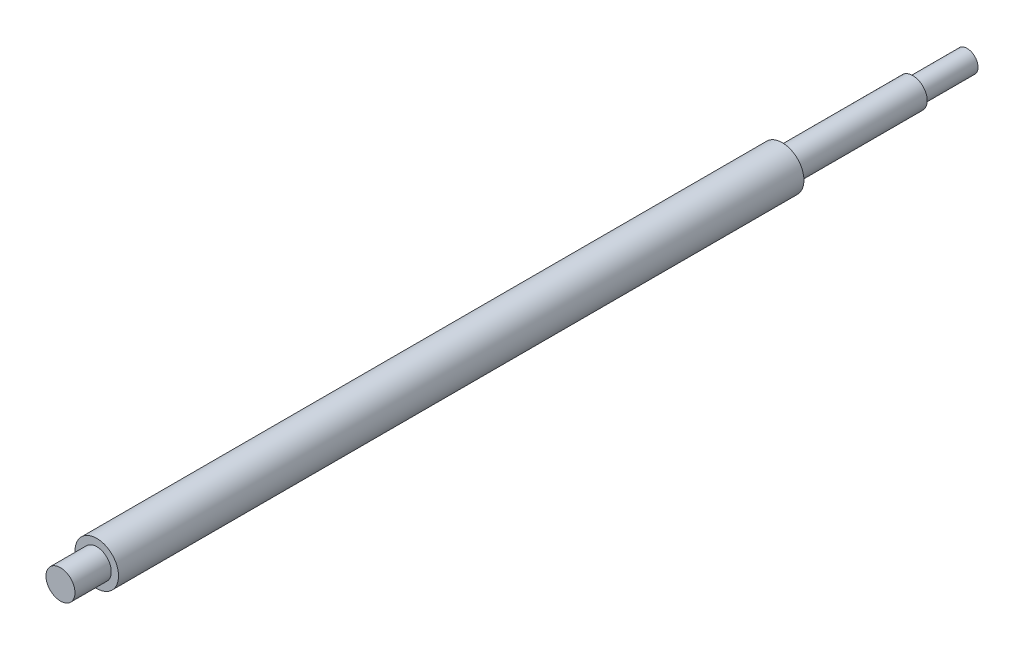
SolidWorks part; units mm, degrees
material "Легированная сталь (SS)"
ref_plane "Front Plane" through (0, 0, 0) normal (0, 0, 1) x (1, 0, 0)
ref_plane "Top Plane" through (0, 0, 0) normal (0, 1, 0) x (1, 0, 0)
ref_plane "Right Plane" through (0, 0, 0) normal (1, 0, 0) x (0, 0, -1)
sketch "Sketch1" plane through (0, 0, 0) normal (0, 0, 1) x (1, 0, 0)
  circle A0 centre (0, 0) radius 6
extrude "Boss-Extrude1" add sketch "Sketch1" along normal blind 250
sketch "Sketch2" plane through (0, 0, 0) normal (0, 0, -1) x (-1, 0, 0)
  circle A1 centre (0, 0) radius 3
  dimension "D1" = 6
extrude "6mm" cut sketch "Sketch2" against normal blind 15 flip side to cut
sketch "Sketch3" plane through (0, 0, 0) normal (0, 0, -1) x (-1, 0, 0)
  circle A1 centre (0, 0) radius 4
  dimension "D1" = 8
extrude "8mm" cut sketch "Sketch3" against normal blind 51 flip side to cut
sketch "Sketch4" plane through (0, 0, 250) normal (0, 0, 1) x (1, 0, 0)
  circle A1 centre (0, 0) radius 4
  dimension "D1" = 8
extrude "8mm-Idle" cut sketch "Sketch4" against normal blind 10 flip side to cut
